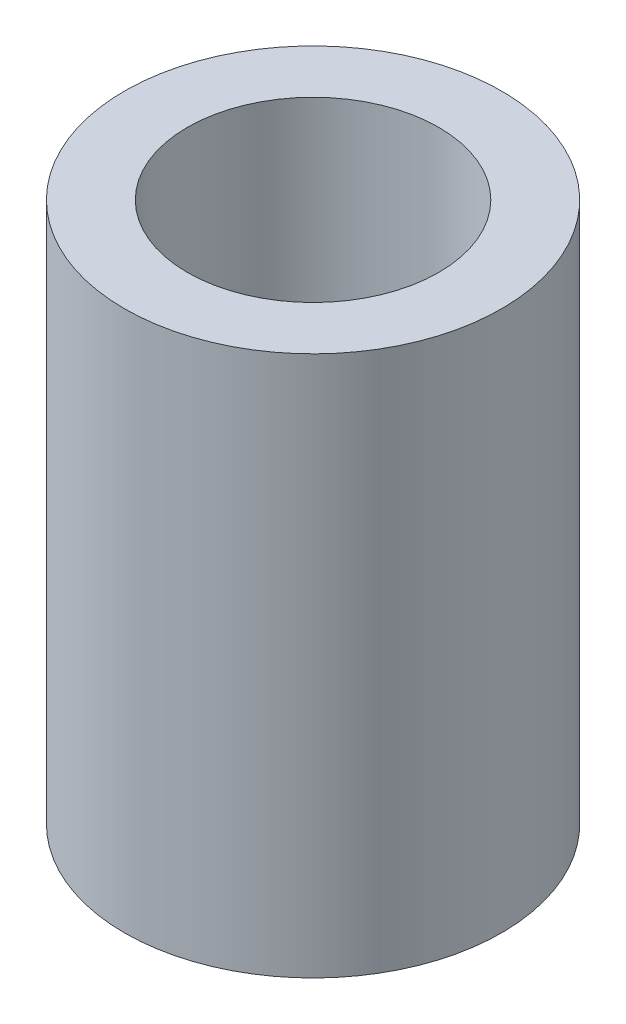
SolidWorks part; units mm, degrees
ref_plane "前视基准面" through (0, 0, 0) normal (0, 0, 1) x (1, 0, 0)
ref_plane "上视基准面" through (0, 0, 0) normal (0, 1, 0) x (1, 0, 0)
ref_plane "右视基准面" through (0, 0, 0) normal (1, 0, 0) x (0, 0, -1)
other "Configuration Table"
sketch "草图1" plane through (0, 0, 0) normal (0, 1, 0) x (1, 0, 0)
  circle A0 centre (0, 0) radius 5
  circle A1 centre (0, 0) radius 7.5
  dimension "D1" = 10
  dimension "D2" = 15
extrude "凸台-拉伸1" add sketch "草图1" along normal blind 21.5
